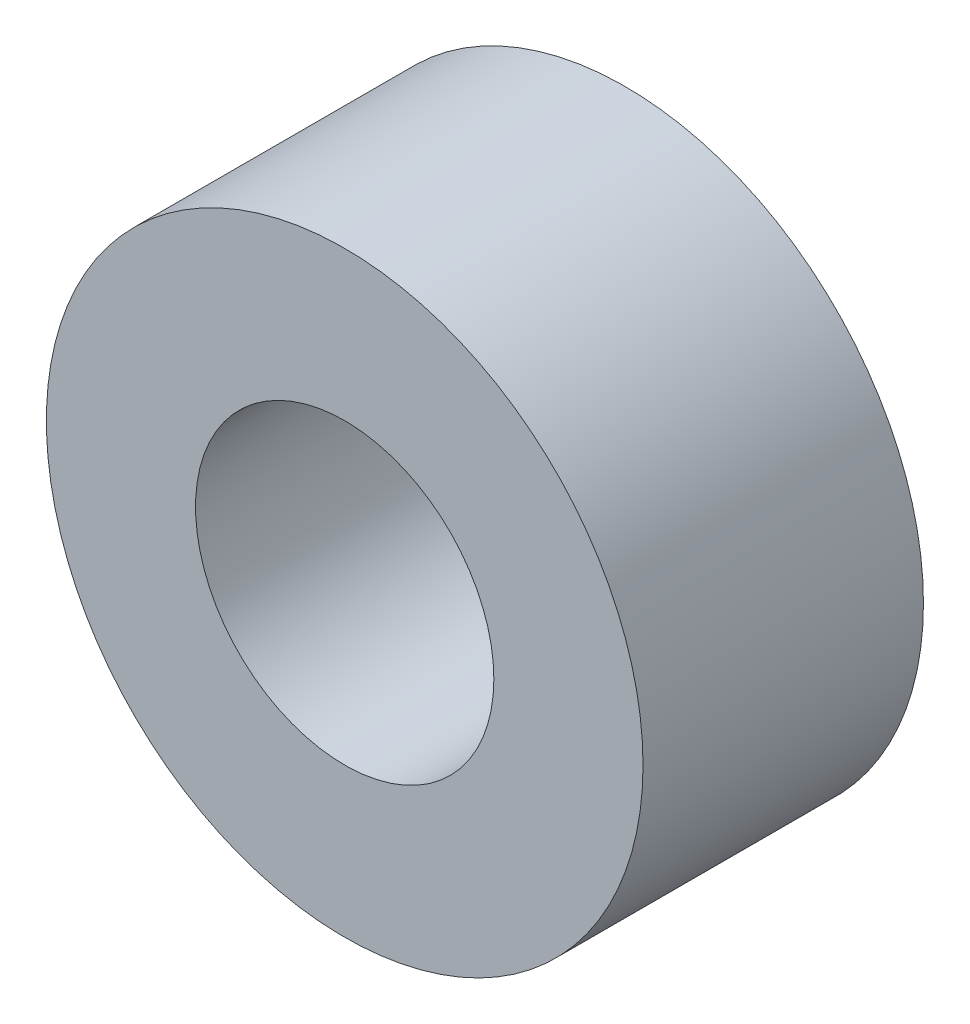
SolidWorks part; units mm, degrees
material "ABS"
ref_plane "Front Plane" through (0, 0, 0) normal (0, 0, 1) x (1, 0, 0)
ref_plane "Top Plane" through (0, 0, 0) normal (0, 1, 0) x (1, 0, 0)
ref_plane "Right Plane" through (0, 0, 0) normal (1, 0, 0) x (0, 0, -1)
sketch "Sketch1" plane through (0, 0, 0) normal (0, 0, 1) x (1, 0, 0)
  circle A0 centre (0, 0) radius 1.5875
  circle A1 centre (0, 0) radius 3.175
  dimension "D1" = 3.175
  dimension "D2" = 6.35
extrude "Boss-Extrude2" add sketch "Sketch1" along normal blind 2.9845 contours A1 | A0
